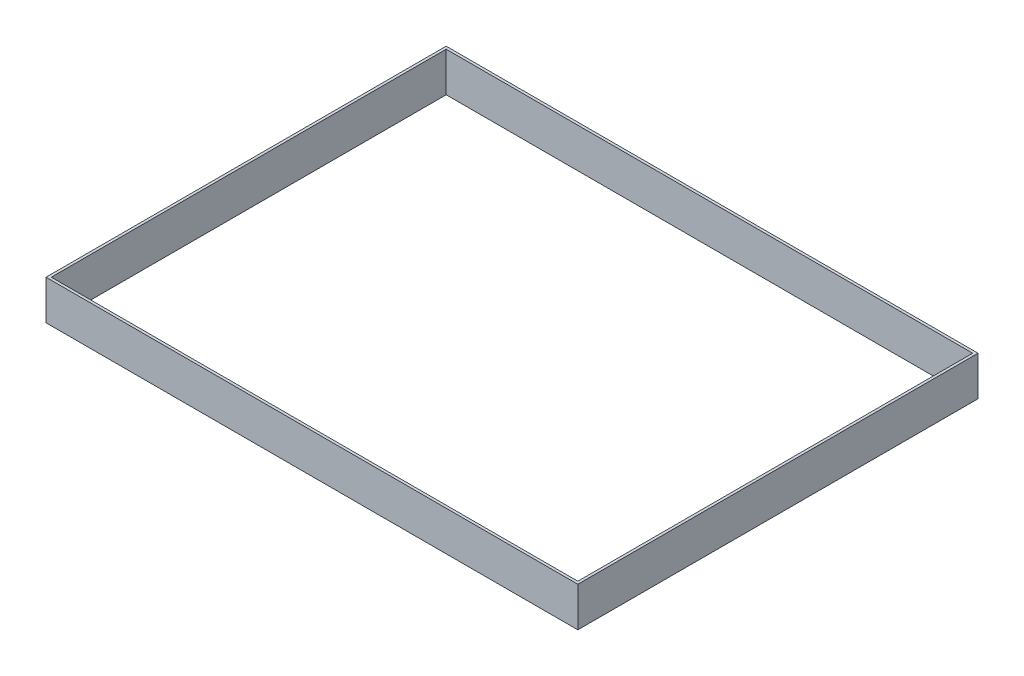
SolidWorks part; units mm, degrees
ref_plane "前视基准面" through (0, 0, 0) normal (0, 0, 1) x (1, 0, 0)
ref_plane "上视基准面" through (0, 0, 0) normal (0, 1, 0) x (1, 0, 0)
ref_plane "右视基准面" through (0, 0, 0) normal (1, 0, 0) x (0, 0, -1)
other "Configuration Table"
sketch "草图1" plane through (0, 0, 0) normal (0, 1, 0) x (1, 0, 0)
  line L0 (-20.2, 15.2) -> (-20.2, -15.2)
  line L5 (-20, 15) -> (20, 15)
  line L6 (-20, 15) -> (-20, -15)
  line L7 (-20, -15) -> (20, -15)
  line L8 (20, 15) -> (20, -15)
  line L9 (-20, 15) -> (20, -15) construction
  line L10 (-20, -15) -> (20, 15) construction
  line L11 (-20.2, -15.2) -> (20.2, -15.2)
  line L12 (20.2, 15.2) -> (20.2, -15.2)
  line L13 (-20.2, 15.2) -> (20.2, 15.2)
  point P0 (0, 0)
  dimension "D1" = 30
  dimension "D2" = 40
  dimension "D3" = 0.2
extrude "凸台-拉伸1" add sketch "草图1" along normal blind 3
